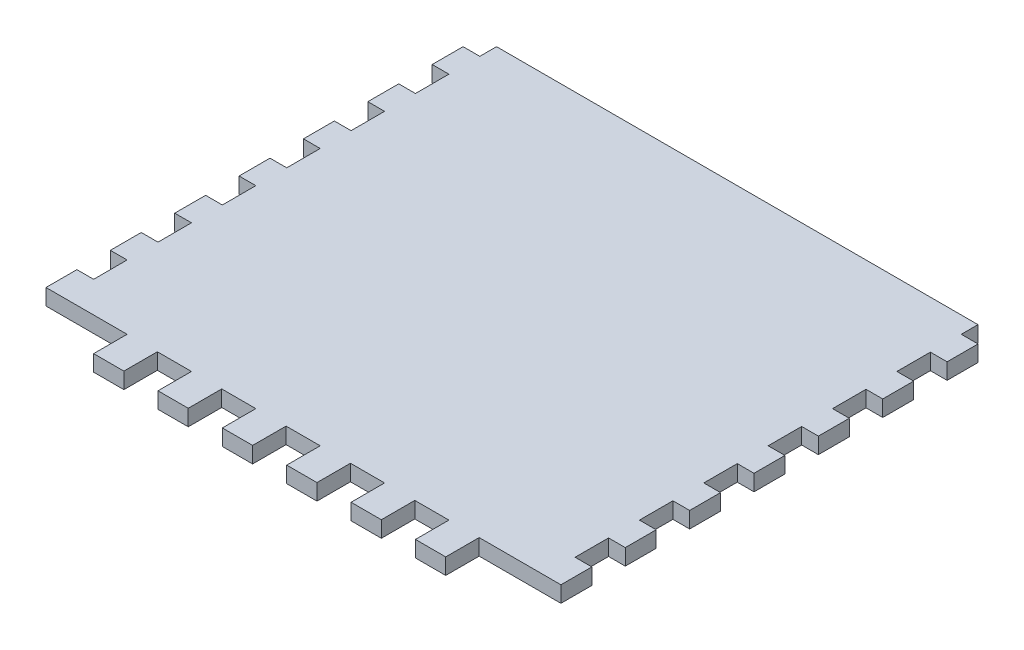
SolidWorks part; units mm, degrees
ref_plane "Front Plane" through (0, 0, 0) normal (0, 0, 1) x (1, 0, 0)
ref_plane "Top Plane" through (0, 0, 0) normal (0, 1, 0) x (1, 0, 0)
ref_plane "Right Plane" through (0, 0, 0) normal (1, 0, 0) x (0, 0, -1)
sketch "Sketch1" plane through (0, 0, 0) normal (0, 1, 0) x (1, 0, 0)
  line L1 (-50.8, -53.975) -> (50.8, -53.975)
  line L2 (-50.8, -53.975) -> (-50.8, 53.975)
  line L3 (-50.8, 53.975) -> (50.8, 53.975)
  line L4 (50.8, -53.975) -> (50.8, 53.975)
  line L5 (-50.8, -53.975) -> (50.8, 53.975) construction
  line L6 (-50.8, 53.975) -> (50.8, -53.975) construction
  point P0 (0, 0)
  dimension "D1" = 101.6
  dimension "D2" = 107.95
extrude "Boss-Extrude1" add sketch "Sketch1" along normal blind 3.175
sketch "Sketch2" plane through (0, 0, 0) normal (0, -1, 0) x (1, 0, 0)
  line L0 (-34.798, 31.623) -> (-47.498, 31.623)
  line L5 (50.8, 53.975) -> (50.8, -53.975) construction
  line L34 (0, 0) -> (0, -14.8721) construction
  line L39 (50.8, 25.527) -> (47.498, 25.527)
  line L41 (50.8, 38.227) -> (50.8, 31.623)
  line L42 (50.8, 31.623) -> (47.498, 31.623)
  line L44 (50.8, 25.527) -> (50.8, 18.923)
  line L45 (50.8, 18.923) -> (47.498, 18.923)
  line L46 (47.498, 25.527) -> (47.498, 18.923)
  line L47 (50.8, 12.827) -> (47.498, 12.827)
  line L48 (50.8, 12.827) -> (50.8, 6.223)
  line L49 (50.8, 6.223) -> (47.498, 6.223)
  line L50 (47.498, 12.827) -> (47.498, 6.223)
  line L51 (50.8, 0.127) -> (47.498, 0.127)
  line L52 (50.8, 0.127) -> (50.8, -6.477)
  line L53 (50.8, -6.477) -> (47.498, -6.477)
  line L54 (47.498, 0.127) -> (47.498, -6.477)
  line L55 (50.8, -12.573) -> (47.498, -12.573)
  line L56 (50.8, -12.573) -> (50.8, -19.177)
  line L57 (50.8, -19.177) -> (47.498, -19.177)
  line L58 (47.498, -12.573) -> (47.498, -19.177)
  line L59 (50.8, -25.273) -> (47.498, -25.273)
  line L60 (50.8, -25.273) -> (50.8, -31.877)
  line L61 (50.8, -31.877) -> (47.498, -31.877)
  line L62 (47.498, -25.273) -> (47.498, -31.877)
  line L63 (50.8, -37.973) -> (47.498, -37.973)
  line L64 (50.8, -37.973) -> (50.8, -44.577)
  line L65 (50.8, -44.577) -> (47.498, -44.577)
  line L66 (47.498, -37.973) -> (47.498, -44.577)
  line L67 (50.8, -50.673) -> (47.498, -50.673)
  line L68 (50.8, -50.673) -> (50.8, -57.277)
  line L69 (50.8, -57.277) -> (47.498, -57.277)
  line L70 (47.498, -50.673) -> (47.498, -57.277)
  line L71 (-47.498, -50.673) -> (-47.498, -57.277)
  line L72 (-50.8, -57.277) -> (-47.498, -57.277)
  line L73 (-50.8, -50.673) -> (-50.8, -57.277)
  line L74 (-50.8, -50.673) -> (-47.498, -50.673)
  line L75 (-47.498, -37.973) -> (-47.498, -44.577)
  line L76 (-50.8, -44.577) -> (-47.498, -44.577)
  line L77 (-50.8, -37.973) -> (-50.8, -44.577)
  line L78 (-50.8, -37.973) -> (-47.498, -37.973)
  line L79 (-47.498, -25.273) -> (-47.498, -31.877)
  line L80 (-50.8, -31.877) -> (-47.498, -31.877)
  line L81 (-50.8, -25.273) -> (-50.8, -31.877)
  line L82 (-50.8, -25.273) -> (-47.498, -25.273)
  line L83 (-47.498, -12.573) -> (-47.498, -19.177)
  line L84 (-50.8, -19.177) -> (-47.498, -19.177)
  line L85 (-50.8, -12.573) -> (-50.8, -19.177)
  line L86 (-50.8, -12.573) -> (-47.498, -12.573)
  line L87 (-47.498, 0.127) -> (-47.498, -6.477)
  line L88 (-50.8, -6.477) -> (-47.498, -6.477)
  line L89 (-50.8, 0.127) -> (-50.8, -6.477)
  line L90 (-50.8, 0.127) -> (-47.498, 0.127)
  line L91 (-47.498, 12.827) -> (-47.498, 6.223)
  line L92 (-50.8, 6.223) -> (-47.498, 6.223)
  line L93 (-50.8, 12.827) -> (-50.8, 6.223)
  line L94 (-50.8, 12.827) -> (-47.498, 12.827)
  line L95 (-47.498, 25.527) -> (-47.498, 18.923)
  line L96 (-50.8, 18.923) -> (-47.498, 18.923)
  line L97 (-50.8, 25.527) -> (-50.8, 18.923)
  line L99 (-50.8, 31.623) -> (-47.498, 31.623)
  line L100 (-50.8, 38.227) -> (-50.8, 31.623)
  line L102 (-50.8, 25.527) -> (-47.498, 25.527)
  line L103 (47.498, 31.623) -> (34.671, 31.623)
  line L104 (34.671, 31.623) -> (34.671, 38.227)
  line L106 (34.671, 38.227) -> (28.702, 38.227)
  line L107 (28.702, 38.227) -> (28.702, 31.623)
  line L108 (28.702, 31.623) -> (21.971, 31.623)
  line L109 (21.971, 31.623) -> (21.971, 38.227)
  line L110 (21.971, 38.227) -> (16.002, 38.227)
  line L111 (16.002, 38.227) -> (16.002, 31.623)
  line L112 (16.002, 31.623) -> (9.271, 31.623)
  line L113 (9.271, 31.623) -> (9.271, 38.227)
  line L114 (9.271, 38.227) -> (3.302, 38.227)
  line L115 (3.302, 38.227) -> (3.302, 31.623)
  line L116 (3.302, 31.623) -> (-3.429, 31.623)
  line L117 (-3.429, 31.623) -> (-3.429, 38.227)
  line L118 (-3.429, 38.227) -> (-9.398, 38.227)
  line L119 (-9.398, 38.227) -> (-9.398, 31.623)
  line L120 (-9.398, 31.623) -> (-16.129, 31.623)
  line L121 (-16.129, 31.623) -> (-16.129, 38.227)
  line L122 (-16.129, 38.227) -> (-22.098, 38.227)
  line L123 (-22.098, 38.227) -> (-22.098, 31.623)
  line L124 (-22.098, 31.623) -> (-28.829, 31.623)
  line L125 (-28.829, 31.623) -> (-28.829, 38.227)
  line L126 (-28.829, 38.227) -> (-34.798, 38.227)
  line L127 (-34.798, 38.227) -> (-34.798, 31.623)
  line L137 (-50.8, 38.227) -> (-50.8, 53.975)
  line L138 (50.8, -53.975) -> (-50.8, -53.975) construction
  line L139 (-50.8, 53.975) -> (50.8, 53.975)
  line L140 (50.8, 53.975) -> (50.8, 38.227)
  point P3 (41.0845, 31.623)
  dimension "D1" = 16.129
  dimension "D2" = 6.604
  dimension "D3" = 5.969
  dimension "D4" = 85.598
  dimension "D5" = 28.829
  dimension "D6" = 41.529
  dimension "D7" = 54.229
  dimension "D8" = 3.302
  dimension "D10" = 66.929
  dimension "D11" = 79.629
  dimension "D9" = 8
extrude "Cut-Extrude1" cut sketch "Sketch2" against normal through all
